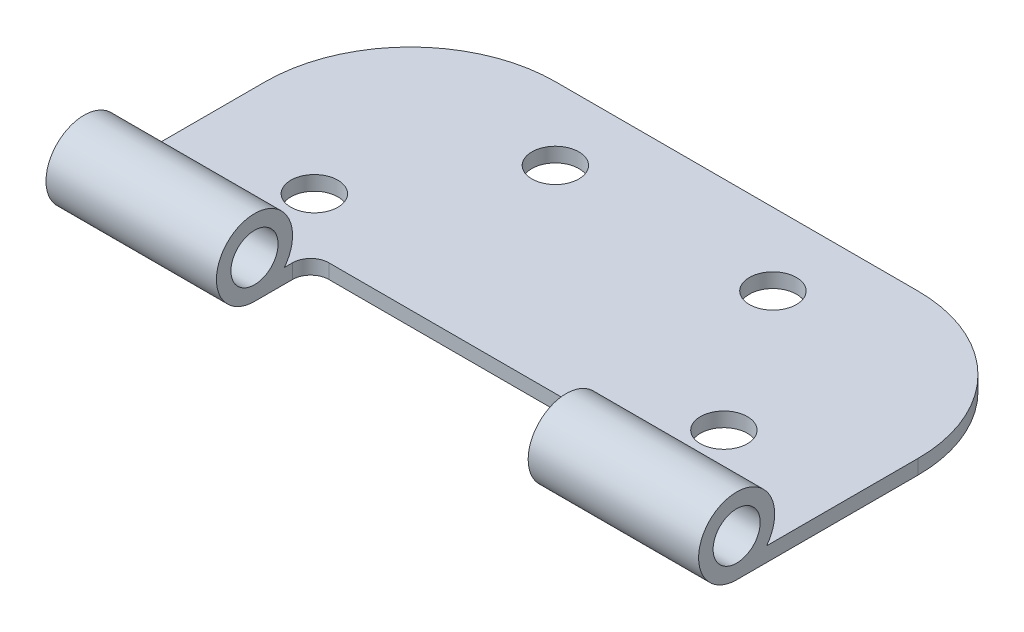
SolidWorks part; units mm, degrees
ref_plane "Спереди" through (0, 0, 0) normal (0, 0, 1) x (1, 0, 0)
ref_plane "Сверху" through (0, 0, 0) normal (0, 1, 0) x (1, 0, 0)
ref_plane "Справа" through (0, 0, 0) normal (1, 0, 0) x (0, 0, -1)
other "Configuration Table"
sketch "Эскиз1" plane through (0, 0, 0) normal (0, 1, 0) x (1, 0, 0)
  line L0 (-45, 2.5) -> (45, 2.5) construction
  line L1 (-25, 22.5) -> (25, 22.5)
  line L2 (-45, 2.5) -> (-45, -22.5)
  line L3 (-45, -22.5) -> (45, -22.5)
  line L4 (45, 2.5) -> (45, -22.5)
  line L5 (-45, 22.5) -> (45, -22.5) construction
  line L6 (-45, -22.5) -> (45, 22.5) construction
  line L7 (-25, 22.5) -> (-25, -22.5) construction
  line L8 (25, 22.5) -> (25, -22.5) construction
  line L9 (0, 22.5) -> (0, -22.5) construction
  arc A0 (45, 2.5) -> (25, 22.5) centre (25, 2.5) ccw
  arc A1 (-25, 22.5) -> (-45, 2.5) centre (-25, 2.5) ccw
  circle A2 centre (-28.24, -7.5) radius 3.24
  circle A3 centre (-15, 12.5) radius 3.24
  circle A4 centre (15, 12.5) radius 3.24
  circle A5 centre (28.24, -7.5) radius 3.24
  point P0 (0, 0)
  dimension "D3" = 20
  dimension "D4" = 6.48
  dimension "D1" = 90
  dimension "D2" = 45
  dimension "D5" = 10
  dimension "D6" = 10
  dimension "D7" = 10
extrude "Бобышка-Вытянуть1" add sketch "Эскиз1" along normal blind 2
sketch "Эскиз2" plane through (45, 0, 0) normal (1, 0, 0) x (0, 0, -1)
  line L0 (-22.5, 5.25) -> (-22.5, 0) construction
  circle A0 centre (-22.5, 5.25) radius 5.25
  circle A1 centre (-22.5, 5.25) radius 3.25
  dimension "D1" = 10.5
  dimension "D2" = 2
  dimension "D3" = 22.5
extrude "Бобышка-Вытянуть2" add sketch "Эскиз2" against normal up to surface (90 mm away) up to face at (-45, 1, 10)
sketch "Эскиз3" plane through (0, 2, 0) normal (0, 1, 0) x (1, 0, 0)
  line L0 (-45, -27.75) -> (45, -27.75) construction
  line L1 (-21.495, -40.75) -> (21.495, -40.75)
  line L2 (-21.495, -40.75) -> (-21.495, -17.25)
  line L3 (-18.995, -14.75) -> (18.995, -14.75)
  line L4 (21.495, -40.75) -> (21.495, -17.25)
  line L5 (-21.495, -40.75) -> (21.495, -14.75) construction
  line L6 (-21.495, -14.75) -> (21.495, -40.75) construction
  arc A0 (21.495, -17.25) -> (18.995, -14.75) centre (18.995, -17.25) ccw
  arc A1 (-21.495, -17.25) -> (-18.995, -14.75) centre (-18.995, -17.25) cw
  point P0 (0, -27.75)
  dimension "D3" = 2.5
  dimension "D1" = 13
  dimension "D2" = 42.99
extrude "Вырез-Вытянуть1" cut sketch "Эскиз3" against normal through all both and the other way through all
